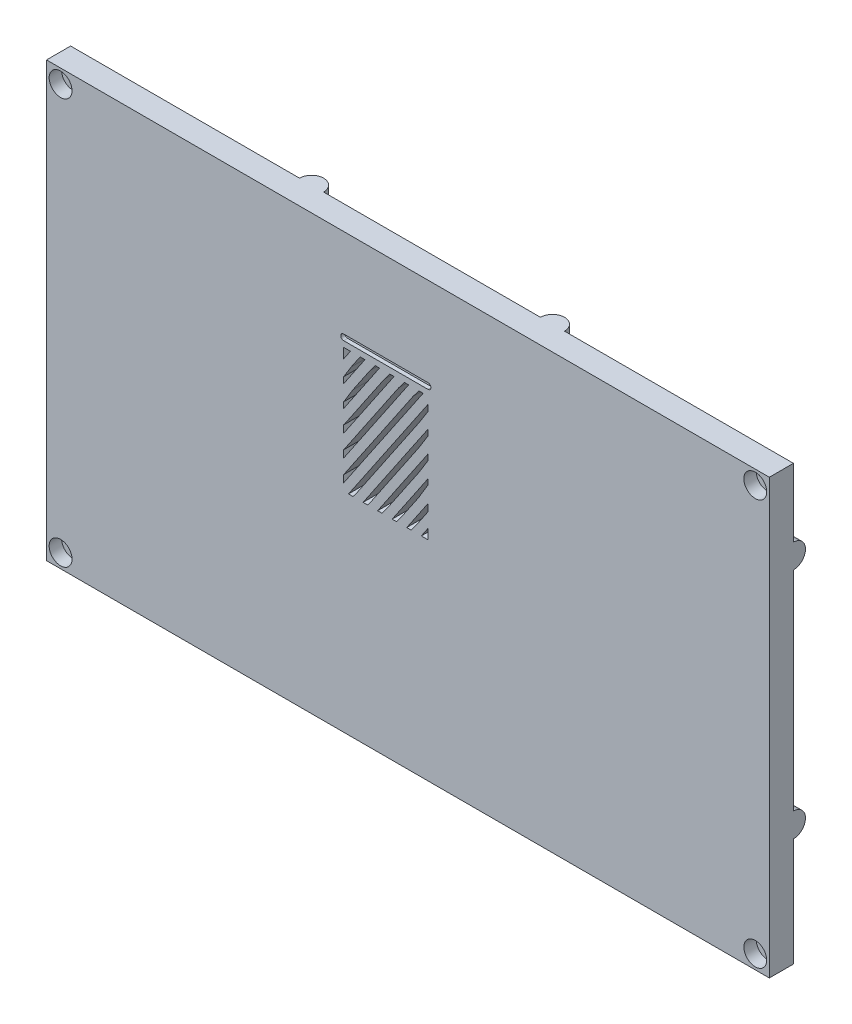
SolidWorks part; units mm, degrees
material "PBT 一般用途"
ref_plane "前视基准面" through (0, 0, 0) normal (0, 0, 1) x (1, 0, 0)
ref_plane "上视基准面" through (0, 0, 0) normal (0, 1, 0) x (1, 0, 0)
ref_plane "右视基准面" through (0, 0, 0) normal (1, 0, 0) x (0, 0, -1)
sketch "草图1" plane through (0, 0, 0) normal (0, 0, 1) x (1, 0, 0)
  line L4 (-67.3343, 65.024) -> (112.6657, 65.024)
  line L5 (112.6657, 65.024) -> (112.6657, -42.976)
  line L6 (112.6657, -42.976) -> (-67.3343, -42.976)
  line L7 (-67.3343, -42.976) -> (-67.3343, 65.024)
  dimension "D1" = 180
  dimension "D2" = 108
extrude "凸台-拉伸4" add sketch "草图1" along normal blind 6
sketch "草图3" plane through (0, 0, 6) normal (0, 0, 1) x (1, 0, 0)
  line L0 (112.6657, -42.976) -> (112.6657, 65.024) construction
  line L1 (112.6657, 65.024) -> (-67.3343, 65.024) construction
  line L2 (-67.3343, -42.976) -> (112.6657, -42.976) construction
  line L3 (-67.3343, 65.024) -> (-67.3343, -42.976) construction
  circle A0 centre (-63.8343, 61.524) radius 2.85
  circle A1 centre (109.1657, 61.524) radius 2.85
  circle A2 centre (109.1657, -39.476) radius 2.85
  circle A3 centre (-63.8343, -39.476) radius 2.85
  dimension "D3" = 5.7
  dimension "D6" = 5.7
  dimension "D9" = 5.7
  dimension "D12" = 5.7
  dimension "D1" = 3.5
  dimension "D2" = 3.5
  dimension "D4" = 3.5
  dimension "D5" = 3.5
  dimension "D7" = 3.5
  dimension "D8" = 3.5
  dimension "D10" = 3.5
  dimension "D11" = 3.5
extrude "凸台-拉伸8" add sketch "草图3" against normal blind 5.7 contours A1
sketch "草图4" plane through (0, 0, 6) normal (0, 0, 1) x (1, 0, 0)
  line L0 (112.6657, 65.024) -> (-67.3343, 65.024) construction
  line L1 (-67.3343, 65.024) -> (-67.3343, -42.976) construction
  circle A0 centre (-63.8343, 61.524) radius 2.85
  dimension "D3" = 5.7
  dimension "D1" = 3.5
  dimension "D2" = 3.5
extrude "凸台-拉伸9" add sketch "草图4" against normal blind 3.1 contours A0
sketch "草图5" plane through (0, 0, 6) normal (0, 0, 1) x (1, 0, 0)
  line L0 (112.6657, 65.024) -> (-67.3343, 65.024) construction
  line L1 (-67.3343, 65.024) -> (-67.3343, -42.976) construction
  circle A0 centre (-63.8343, 61.524) radius 2.85
  dimension "D3" = 5.7
  dimension "D1" = 3.5
  dimension "D2" = 3.5
extrude "切除-拉伸1" cut sketch "草图5" against normal blind 3.1
sketch "草图7" plane through (0, 0, 6) normal (0, 0, 1) x (1, 0, 0)
  line L0 (112.6657, 65.024) -> (-67.3343, 65.024) construction
  line L1 (112.6657, -42.976) -> (112.6657, 65.024) construction
  circle A0 centre (109.1657, 61.524) radius 2.85
  dimension "D3" = 5.7
  dimension "D1" = 3.5
  dimension "D2" = 3.5
extrude "切除-拉伸2" cut sketch "草图7" against normal blind 3.1
sketch "草图8" plane through (0, 0, 6) normal (0, 0, 1) x (1, 0, 0)
  line L0 (-67.3343, 65.024) -> (-67.3343, -42.976) construction
  line L1 (-67.3343, -42.976) -> (112.6657, -42.976) construction
  circle A0 centre (-63.8343, -39.476) radius 2.85
  dimension "D3" = 5.7
  dimension "D1" = 3.5
  dimension "D2" = 3.5
extrude "切除-拉伸3" cut sketch "草图8" against normal blind 3.1
sketch "草图9" plane through (0, 0, 6) normal (0, 0, 1) x (1, 0, 0)
  line L0 (112.6657, -42.976) -> (112.6657, 65.024) construction
  line L1 (-67.3343, -42.976) -> (112.6657, -42.976) construction
  circle A0 centre (109.1657, -39.476) radius 2.85
  dimension "D3" = 5.7
  dimension "D1" = 3.5
  dimension "D2" = 3.5
extrude "切除-拉伸4" cut sketch "草图9" against normal blind 3.1
sketch "草图10" plane through (0, 0, 0) normal (0, 0, -1) x (-1, 0, 0)
  line L0 (-112.6657, 65.024) -> (67.3343, 65.024) construction
  line L1 (-112.6657, -42.976) -> (-112.6657, 65.024) construction
  circle A0 centre (-109.1657, 61.524) radius 1.51
  dimension "D3" = 3.02
  dimension "D1" = 3.5
  dimension "D2" = 3.5
extrude "切除-拉伸5" cut sketch "草图10" against normal blind 3.1
sketch "草图11" plane through (0, 0, 0) normal (0, 0, -1) x (-1, 0, 0)
  line L0 (-112.6657, -42.976) -> (-112.6657, 65.024) construction
  line L1 (67.3343, -42.976) -> (-112.6657, -42.976) construction
  circle A0 centre (-109.1657, -39.476) radius 1.51
  dimension "D3" = 3.02
  dimension "D1" = 3.5
  dimension "D2" = 3.5
extrude "切除-拉伸6" cut sketch "草图11" against normal blind 3.1
sketch "草图12" plane through (0, 0, 0) normal (0, 0, -1) x (-1, 0, 0)
  line L0 (-112.6657, 65.024) -> (67.3343, 65.024) construction
  line L1 (67.3343, 65.024) -> (67.3343, -42.976) construction
  circle A0 centre (63.8343, 61.524) radius 1.51
  dimension "D3" = 3.02
  dimension "D1" = 3.5
  dimension "D2" = 3.5
extrude "切除-拉伸7" cut sketch "草图12" against normal blind 3.1
sketch "草图13" plane through (0, 0, 0) normal (0, 0, -1) x (-1, 0, 0)
  line L0 (67.3343, 65.024) -> (67.3343, -42.976) construction
  line L1 (67.3343, -42.976) -> (-112.6657, -42.976) construction
  circle A0 centre (63.8343, -39.476) radius 1.51
  dimension "D3" = 3.02
  dimension "D1" = 3.5
  dimension "D2" = 3.5
extrude "切除-拉伸8" cut sketch "草图13" against normal blind 3.1
sketch "草图14" plane through (0, 0, 6) normal (0, 0, 1) x (1, 0, 0)
  line L0 (112.6657, 40.024) -> (27.6657, 40.024)
  line L1 (112.6657, -42.976) -> (112.6657, 65.024) construction
  line L2 (27.6657, 40.024) -> (27.6657, 9.024)
  line L3 (27.6657, 9.024) -> (6.6657, 9.024)
  line L4 (6.6657, 9.024) -> (6.6657, 40.024)
  line L5 (6.6657, 40.024) -> (27.6657, 40.024)
  line L6 (112.6657, 65.024) -> (-67.3343, 65.024) construction
  dimension "D1" = 85
  dimension "D2" = 21
  dimension "D3" = 31
  dimension "D4" = 25
extrude "切除-拉伸10" cut sketch "草图14" against normal blind 10 contours L5 L4 L3 L2
sketch "草图15" plane through (0, 0, 6) normal (0, 0, 1) x (1, 0, 0)
  line L1 (6.6657, 42.1954) -> (27.6657, 42.1954) construction
  line L2 (6.6657, 42.919) -> (27.6657, 42.919)
  line L3 (6.6657, 41.4718) -> (27.6657, 41.4718)
  arc A0 (6.6657, 42.919) -> (6.6657, 41.4718) centre (6.6657, 42.1954) ccw
  arc A1 (27.6657, 41.4718) -> (27.6657, 42.919) centre (27.6657, 42.1954) ccw
  point P1 (17.1657, 42.1954)
extrude "切除-拉伸12" cut sketch "草图15" against normal blind 1
sketch "草图16" plane through (0, 0, 6) normal (0, 0, 1) x (1, 0, 0)
  line L0 (27.6657, 40.024) -> (6.6657, 9.024) construction
  line L1 (28.4937, 39.4632) -> (7.4937, 8.4632)
  line L2 (26.8378, 40.5849) -> (5.8378, 9.5849)
  line L3 (24.0422, 40.024) -> (6.6657, 14.3731) construction
  line L4 (6.6657, 40.024) -> (27.6657, 40.024) construction
  line L5 (6.6657, 9.024) -> (6.6657, 40.024) construction
  line L6 (24.8701, 39.4632) -> (7.4937, 13.8122)
  line L7 (23.2143, 40.5849) -> (5.8378, 14.9339)
  line L8 (20.4187, 40.024) -> (6.6657, 19.7221) construction
  line L11 (21.2466, 39.4632) -> (7.4937, 19.1613)
  line L12 (19.5907, 40.5849) -> (5.8378, 20.283)
  line L13 (16.7951, 40.024) -> (6.6657, 25.0711) construction
  line L14 (17.623, 39.4632) -> (7.4937, 24.5103)
  line L15 (15.9672, 40.5849) -> (5.8378, 25.632)
  line L16 (13.1474, 39.9883) -> (6.6657, 30.4202) construction
  line L17 (13.9753, 39.4274) -> (7.4937, 29.8593)
  line L18 (12.3194, 40.5491) -> (5.8378, 30.981)
  line L19 (9.548, 40.024) -> (6.6657, 35.7692) construction
  line L20 (10.3759, 39.4632) -> (7.4937, 35.2084)
  line L21 (8.7201, 40.5849) -> (5.8378, 36.3301)
  line L22 (27.6657, 34.675) -> (10.2893, 9.024) construction
  line L23 (27.6657, 40.024) -> (27.6657, 9.024) construction
  line L24 (27.6657, 9.024) -> (6.6657, 9.024) construction
  line L25 (28.4937, 34.1141) -> (11.1172, 8.4632)
  line L26 (26.8378, 35.2358) -> (9.4614, 9.5849)
  line L27 (27.6657, 29.3259) -> (13.9128, 9.024) construction
  line L28 (28.4937, 28.7651) -> (14.7408, 8.4632)
  line L29 (26.8378, 29.8868) -> (13.0849, 9.5849)
  line L30 (27.6657, 23.9769) -> (17.5364, 9.024) construction
  line L33 (27.6657, 18.6279) -> (21.0114, 8.8048) construction
  line L34 (28.4937, 18.067) -> (21.8394, 8.244)
  line L35 (26.8378, 19.1887) -> (20.1835, 9.3657)
  line L36 (27.6657, 13.2788) -> (24.7835, 9.024) construction
  line L37 (28.4937, 12.718) -> (25.6114, 8.4632)
  line L38 (26.8378, 13.8397) -> (23.9555, 9.5849)
  line L39 (28.4937, 23.4161) -> (18.3643, 8.4632)
  line L40 (26.8378, 24.5377) -> (16.7085, 9.5849)
  arc A0 (28.4937, 39.4632) -> (26.8378, 40.5849) centre (27.6657, 40.024) ccw
  arc A1 (5.8378, 9.5849) -> (7.4937, 8.4632) centre (6.6657, 9.024) ccw
  arc A2 (24.8701, 39.4632) -> (23.2143, 40.5849) centre (24.0422, 40.024) ccw
  arc A3 (5.8378, 14.9339) -> (7.4937, 13.8122) centre (6.6657, 14.3731) ccw
  arc A6 (21.2466, 39.4632) -> (19.5907, 40.5849) centre (20.4187, 40.024) ccw
  arc A7 (5.8378, 20.283) -> (7.4937, 19.1613) centre (6.6657, 19.7221) ccw
  arc A8 (17.623, 39.4632) -> (15.9672, 40.5849) centre (16.7951, 40.024) ccw
  arc A9 (5.8378, 25.632) -> (7.4937, 24.5103) centre (6.6657, 25.0711) ccw
  arc A10 (13.9753, 39.4274) -> (12.3194, 40.5491) centre (13.1474, 39.9883) ccw
  arc A11 (5.8378, 30.981) -> (7.4937, 29.8593) centre (6.6657, 30.4202) ccw
  arc A12 (10.3759, 39.4632) -> (8.7201, 40.5849) centre (9.548, 40.024) ccw
  arc A13 (5.8378, 36.3301) -> (7.4937, 35.2084) centre (6.6657, 35.7692) ccw
  arc A14 (28.4937, 34.1141) -> (26.8378, 35.2358) centre (27.6657, 34.675) ccw
  arc A15 (9.4614, 9.5849) -> (11.1172, 8.4632) centre (10.2893, 9.024) ccw
  arc A16 (28.4937, 28.7651) -> (26.8378, 29.8868) centre (27.6657, 29.3259) ccw
  arc A17 (13.0849, 9.5849) -> (14.7408, 8.4632) centre (13.9128, 9.024) ccw
  arc A20 (28.4937, 18.067) -> (26.8378, 19.1887) centre (27.6657, 18.6279) ccw
  arc A21 (20.1835, 9.3657) -> (21.8394, 8.244) centre (21.0114, 8.8048) ccw
  arc A22 (28.4937, 12.718) -> (26.8378, 13.8397) centre (27.6657, 13.2788) ccw
  arc A23 (23.9555, 9.5849) -> (25.6114, 8.4632) centre (24.7835, 9.024) ccw
  arc A24 (28.4937, 23.4161) -> (26.8378, 24.5377) centre (27.6657, 23.9769) ccw
  arc A25 (16.7085, 9.5849) -> (18.3643, 8.4632) centre (17.5364, 9.024) ccw
  point P2 (17.1657, 24.524)
  point P15 (15.354, 27.1985)
  point P20 (24.6031, 40.8519)
  point P23 (13.5422, 29.8731)
  point P28 (11.7304, 32.5476)
  point P35 (9.9066, 35.2042)
  point P44 (8.1069, 37.8966)
  point P55 (18.9775, 21.8495)
  point P60 (20.7893, 19.175)
  point P69 (22.6011, 16.5005)
  point P74 (24.3386, 13.7163)
  point P81 (26.2246, 11.1514)
  dimension "D1" = 1
  dimension "D3" = 3
  dimension "D7" = 1
  dimension "D8" = 1
  dimension "D9" = 1
  dimension "D12" = 1
  dimension "D13" = 1
  dimension "D14" = 3
  dimension "D15" = 1
  dimension "D16" = 1
  dimension "D21" = 3
  dimension "D19" = 1
  dimension "D2" = 1
  dimension "D4" = 3
  dimension "D5" = 3
  dimension "D6" = 3
  dimension "D11" = 3
  dimension "D17" = 3
  dimension "D18" = 3
  dimension "D20" = 3
extrude "凸台-拉伸10" add sketch "草图16" against normal blind 4.4 contours L38 A23 L37 A22 | L35 A20 L34 A21 | L40 A25 L39 A24 | L29 A17 L28 A16 | L26 A15 L25 A14 | L2 A1 L1 A0 | L7 A3 L6 A2 | L12 A7 L11 A6 | L15 A9 L14 A8 | L18 A11 L17 A10 | L21 A12 L20 A13
sketch "草图17" plane through (0, 0, 6) normal (0, 0, 1) x (1, 0, 0)
  line L0 (11.6905, 9.3094) -> (10.085, 10.5055)
  line L1 (11.6905, 9.3094) -> (10.1424, 7.2315)
  line L2 (10.085, 10.5055) -> (8.5369, 8.4275)
  line L3 (10.1424, 7.2315) -> (8.5369, 8.4275)
  line L4 (27.6657, 32.892) -> (11.4971, 9.024) construction
  line L5 (26.8378, 35.2358) -> (9.4614, 9.5849) construction
  line L6 (15.1509, 9.0686) -> (13.5454, 10.2647)
  line L7 (15.1509, 9.0686) -> (13.7524, 7.1914)
  line L8 (13.5454, 10.2647) -> (12.1469, 8.3875)
  line L9 (13.7524, 7.1914) -> (12.1469, 8.3875)
  line L10 (27.6657, 27.5429) -> (15.1207, 9.024) construction
  line L11 (26.8378, 29.8868) -> (13.0849, 9.5849) construction
  line L12 (18.9376, 9.3094) -> (17.3321, 10.5055)
  line L13 (18.9376, 9.3094) -> (17.217, 6.9999)
  line L14 (17.3321, 10.5055) -> (15.6115, 8.196)
  line L15 (17.217, 6.9999) -> (15.6115, 8.196)
  line L16 (27.6657, 22.1939) -> (18.7442, 9.024) construction
  line L17 (26.8378, 24.5377) -> (16.7085, 9.5849) construction
  line L18 (22.5134, 9.2389) -> (20.9079, 10.435)
  line L19 (22.5134, 9.2389) -> (20.6163, 6.6926)
  line L20 (20.9079, 10.435) -> (19.0109, 7.8886)
  line L21 (20.6163, 6.6926) -> (19.0109, 7.8886)
  line L22 (27.6657, 16.8448) -> (22.3678, 9.024) construction
  line L23 (26.8378, 19.1887) -> (20.1835, 9.3657) construction
  line L24 (26.1369, 9.2389) -> (24.5315, 10.435)
  line L25 (26.1369, 9.2389) -> (24.349, 6.8391)
  line L26 (24.5315, 10.435) -> (22.7436, 8.0352)
  line L27 (24.349, 6.8391) -> (22.7436, 8.0352)
  line L28 (27.6657, 11.4958) -> (25.9913, 9.024) construction
  line L29 (26.8378, 13.8397) -> (23.9555, 9.5849) construction
  line L46 (22.3237, 39.2702) -> (23.9292, 38.0741)
  line L47 (22.3237, 39.2702) -> (23.7994, 41.251)
  line L48 (23.9292, 38.0741) -> (25.4049, 40.0549)
  line L49 (23.7994, 41.251) -> (25.4049, 40.0549)
  line L50 (22.8344, 40.024) -> (6.6657, 16.1561) construction
  line L51 (24.8701, 39.4632) -> (7.4937, 13.8122) construction
  line L52 (18.7505, 39.3446) -> (20.356, 38.1485)
  line L53 (18.7505, 39.3446) -> (20.2941, 41.4165)
  line L54 (20.356, 38.1485) -> (21.8995, 40.2204)
  line L55 (20.2941, 41.4165) -> (21.8995, 40.2204)
  line L56 (19.2108, 40.024) -> (6.6657, 21.5051) construction
  line L57 (21.2466, 39.4632) -> (7.4937, 19.1613) construction
  line L58 (15.1509, 39.3799) -> (16.7535, 38.1796)
  line L59 (15.1509, 39.3799) -> (16.5987, 41.3129)
  line L60 (16.7535, 38.1796) -> (18.2013, 40.1126)
  line L61 (16.5987, 41.3129) -> (18.2013, 40.1126)
  line L62 (15.5873, 40.024) -> (6.6657, 26.8542) construction
  line L63 (17.623, 39.4632) -> (7.4937, 24.5103) construction
  line L64 (11.5806, 39.4585) -> (13.1832, 38.2582)
  line L65 (11.5806, 39.4585) -> (13.0495, 41.4197)
  line L66 (13.1832, 38.2582) -> (14.6521, 40.2194)
  line L67 (13.0495, 41.4197) -> (14.6521, 40.2194)
  line L68 (11.9637, 40.024) -> (6.6657, 32.2032) construction
  line L69 (13.9753, 39.4274) -> (7.4937, 29.8593) construction
  line L74 (7.4079, 17.2517) -> (9.0638, 16.13)
  line L75 (7.4079, 17.2517) -> (4.3954, 12.8046)
  line L76 (9.0638, 16.13) -> (6.0512, 11.6829)
  line L77 (4.3954, 12.8046) -> (6.0512, 11.6829)
  line L78 (7.2357, 22.3464) -> (8.8915, 21.2247)
  line L79 (7.2357, 22.3464) -> (4.3528, 18.0907)
  line L80 (8.8915, 21.2247) -> (6.0086, 16.969)
  line L81 (4.3528, 18.0907) -> (6.0086, 16.969)
  line L82 (7.2357, 27.6955) -> (8.8915, 26.5738)
  line L83 (7.2357, 27.6955) -> (5.0522, 24.4723)
  line L84 (8.8915, 26.5738) -> (6.7081, 23.3506)
  line L85 (5.0522, 24.4723) -> (6.7081, 23.3506)
  line L86 (7.2357, 33.0445) -> (8.9416, 31.9968)
  line L87 (7.2357, 33.0445) -> (4.8764, 29.203)
  line L88 (8.9416, 31.9968) -> (6.5824, 28.1553)
  line L89 (4.8764, 29.203) -> (6.5824, 28.1553)
  line L90 (6.831, 37.7962) -> (8.5369, 36.7485)
  line L91 (6.831, 37.7962) -> (4.6536, 34.2507)
  line L92 (8.5369, 36.7485) -> (6.3595, 33.203)
  line L93 (4.6536, 34.2507) -> (6.3595, 33.203)
  line L94 (8.3402, 40.024) -> (6.6657, 37.5522) construction
  line L95 (10.3759, 39.4632) -> (7.4937, 35.2084) construction
  line L96 (7.9038, 39.3799) -> (9.5596, 38.2582)
  line L97 (7.9038, 39.3799) -> (9.2911, 41.4277)
  line L98 (9.5596, 38.2582) -> (10.9469, 40.306)
  line L99 (9.2911, 41.4277) -> (10.9469, 40.306)
  line L100 (27.0593, 31.9968) -> (25.3696, 33.0684)
  line L101 (27.0593, 31.9968) -> (29.5928, 35.9918)
  line L102 (25.3696, 33.0684) -> (27.903, 37.0634)
  line L103 (29.5928, 35.9918) -> (27.903, 37.0634)
  line L108 (27.0593, 26.6478) -> (25.3585, 27.703)
  line L109 (27.0593, 26.6478) -> (29.6575, 30.8357)
  line L110 (25.3585, 27.703) -> (27.9566, 31.8909)
  line L111 (29.6575, 30.8357) -> (27.9566, 31.8909)
  line L112 (27.0593, 21.2987) -> (25.355, 22.3488)
  line L113 (27.0593, 21.2987) -> (29.8097, 25.7629)
  line L114 (25.355, 22.3488) -> (28.1054, 26.813)
  line L115 (29.8097, 25.7629) -> (28.1054, 26.813)
  line L116 (27.0593, 15.9497) -> (25.3407, 16.9787)
  line L117 (27.0593, 15.9497) -> (29.8756, 20.6533)
  line L118 (25.3407, 16.9787) -> (28.157, 21.6823)
  line L119 (29.8756, 20.6533) -> (28.157, 21.6823)
  line L120 (27.4008, 11.1046) -> (25.7449, 12.2263)
  line L121 (27.4008, 11.1046) -> (30.0937, 15.0799)
  line L122 (25.7449, 12.2263) -> (28.4379, 16.2016)
  line L123 (30.0937, 15.0799) -> (28.4379, 16.2016)
extrude "凸台-拉伸12" add sketch "草图17" against normal blind 4.4 contours L99 L97 L96 L98 | L67 L65 L64 L66 | L61 L59 L58 L60 | L49 L47 L46 L48 | L55 L53 L52 L54 | L101 L103 L102 L100 | L109 L111 L110 L108 | L113 L115 L114 L112 | L117 L119 L118 L116 | L121 L123 L122 L120 | L27 L25 L24 L26 | L21 L19 L18 L20 | L15 L13 L12 L14 | L9 L7 L6 L8 | L3 L1 L0 L2 | L75 L77 L76 L74 | L79 L81 L80 L78 | L83 L85 L84 L82 | L87 L89 L88 L86 | L90 L91 L93 L92
sketch "草图18" plane through (0, 65.024, 0) normal (0, 1, 0) x (1, 0, 0)
  line L0 (112.6657, 0) -> (-67.3343, 0) construction
  line L1 (-67.3343, 0) -> (-7.3343, 0)
  line L2 (-7.3343, 0) -> (-52.5588, 0)
  line L3 (-52.5588, 0) -> (-50.382, 0)
  line L4 (-7.3343, 0) -> (52.6657, 0)
  circle A0 centre (-7.3343, 0) radius 3
  circle A1 centre (52.6657, 0) radius 3
  dimension "D2" = 6
  dimension "D4" = 6
  dimension "D1" = 60
  dimension "D3" = 60
extrude "凸台-拉伸15" add sketch "草图18" against normal blind 108 contours A0 | A1
sketch "草图21" plane through (112.6657, 0, 0) normal (1, 0, 0) x (0, 0, -1)
  line L0 (0, -42.976) -> (0, -12.976)
  line L1 (0, -42.976) -> (0, 65.024) construction
  line L2 (0, 65.024) -> (0, 45.024)
  circle A0 centre (0, -12.976) radius 3
  circle A1 centre (0, 45.024) radius 3
  dimension "D2" = 6
  dimension "D4" = 6
  dimension "D1" = 30
  dimension "D3" = 20
extrude "凸台-拉伸16" add sketch "草图21" against normal blind 180 contours A0 | A1
